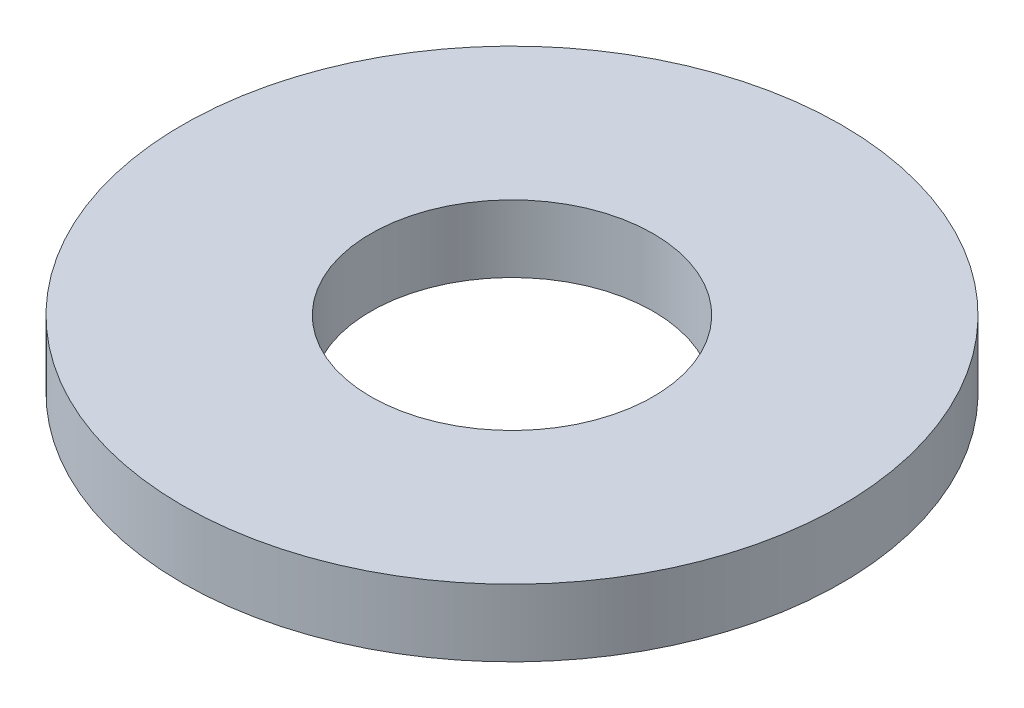
SolidWorks part; units mm, degrees
ref_plane "Front Plane" through (0, 0, 0) normal (0, 0, 1) x (1, 0, 0)
ref_plane "Top Plane" through (0, 0, 0) normal (0, 1, 0) x (1, 0, 0)
ref_plane "Right Plane" through (0, 0, 0) normal (1, 0, 0) x (0, 0, -1)
sketch "Sketch1" plane through (0, 0, 0) normal (0, 1, 0) x (1, 0, 0)
  circle A0 centre (0, 0) radius 2.45
  circle A1 centre (0, 0) radius 1.05
  dimension "D2" = 2.1
  dimension "D1" = 4.9
extrude "Boss-Extrude1" add sketch "Sketch1" along normal blind 0.5
equation "\"M\" = 2mm"
equation "\"D2@Sketch1\"=\"M\"+0.1"
equation "\"D1@Sketch1\"=\"M\"*2+0.9"
